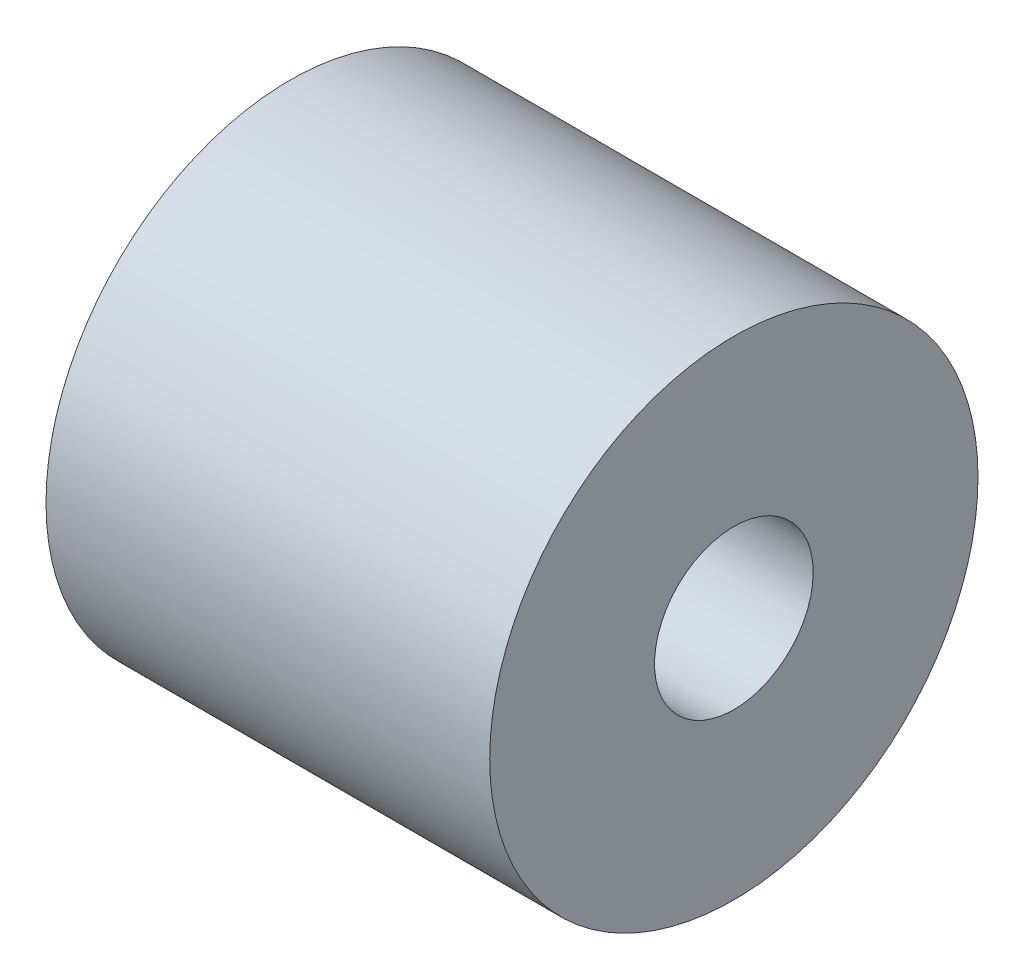
SolidWorks part; units mm, degrees
ref_plane "Front Plane" through (0, 0, 0) normal (0, 0, 1) x (1, 0, 0)
ref_plane "Top Plane" through (0, 0, 0) normal (0, 1, 0) x (1, 0, 0)
ref_plane "Right Plane" through (0, 0, 0) normal (1, 0, 0) x (0, 0, -1)
sketch "Sketch1" plane through (0, 0, 0) normal (1, 0, 0) x (0, 0, -1)
  circle A0 centre (0, 0) radius 10
  circle A1 centre (0, 0) radius 3.25
  dimension "D1" = 6.5
  dimension "D2" = 20
extrude "Boss-Extrude1" add sketch "Sketch1" along normal blind 18.175
